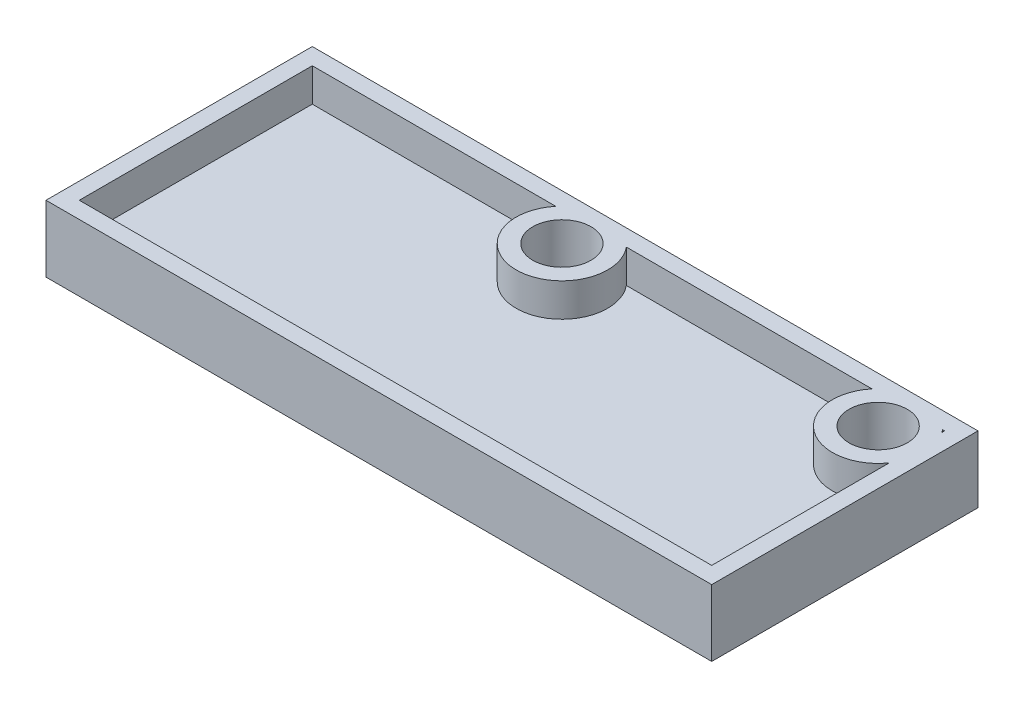
SolidWorks part; units mm, degrees
ref_plane "Front Plane" through (0, 0, 0) normal (0, 0, 1) x (1, 0, 0)
ref_plane "Top Plane" through (0, 0, 0) normal (0, 1, 0) x (1, 0, 0)
ref_plane "Right Plane" through (0, 0, 0) normal (1, 0, 0) x (0, 0, -1)
sketch "Sketch1" plane through (0, 0, 0) normal (0, 1, 0) x (1, 0, 0)
  line L1 (0, 0) -> (40, 0)
  line L2 (0, 0) -> (0, 16)
  line L3 (0, 16) -> (40, 16)
  line L4 (40, 0) -> (40, 16)
  dimension "D1" = 40
  dimension "D2" = 16
extrude "Boss-Extrude1" add sketch "Sketch1" along normal blind 2
sketch "Sketch2" plane through (0, 2, 0) normal (0, 1, 0) x (1, 0, 0)
  line L1 (0, 0) -> (40, 0)
  line L2 (0, 0) -> (0, 16)
  line L3 (0, 16) -> (40, 16)
  line L4 (40, 0) -> (40, 16)
  line L5 (1, 1) -> (39, 1)
  line L6 (1, 1) -> (1, 15)
  line L7 (1, 15) -> (39, 15)
  line L8 (39, 1) -> (39, 15)
  dimension "D1" = 1
  dimension "D2" = 1
  dimension "D3" = 14
  dimension "D4" = 38
extrude "Boss-Extrude2" add sketch "Sketch2" along normal blind 2
sketch "Sketch3" plane through (0, 4, 0) normal (0, 1, 0) x (1, 0, 0)
  line L0 (17.75, 13.25) -> (17.75, 16)
  line L1 (17.75, 16) -> (40, 16)
  line L2 (40, 16) -> (40, 0)
  line L3 (40, 0) -> (0.5, 0)
  line L4 (0.5, 0) -> (0.5, 16)
  line L5 (0.5, 16) -> (17.75, 16)
  line L6 (36.75, 16) -> (36.75, 13.25)
  line L7 (17.75, 13.25) -> (36.75, 13.25)
  line L8 (36.75, 13.25) -> (40, 13.25)
  line L9 (0, 0) -> (40, 0) construction
  line L10 (40, 0) -> (40, 16) construction
  circle A0 centre (36.75, 13.25) radius 1.75
  circle A1 centre (17.75, 13.25) radius 1.75
  circle A2 centre (17.75, 13.25) radius 2.75
  circle A3 centre (36.75, 13.25) radius 2.75
  line M18 (1, 15) -> (39, 15)
  line M19 (39, 15) -> (39, 1)
  dimension "D3" = 3.5
  dimension "D7" = 3.5
  dimension "D1" = 3.25
  dimension "D2" = 2.75
  dimension "D4" = 16
  dimension "D5" = 39.5
  dimension "D6" = 17.25
  dimension "D8" = 0
  dimension "D9" = 0
  dimension "D10" = 2.75
extrude "Boss-Extrude5" add sketch "Sketch3" against normal up to next contours L7 A0 L8 | L8 A0 L6 | L6 A0 L7 | L0 A1 L7 | L7 A1 L0 | A3 L6 M18 | A3 L8 M19 | L8 A3 M19 | L6 A3 M18 | A2 L0 M18 | L0 A2 M18
sketch "Sketch4" plane through (0, 4, 0) normal (0, 1, 0) x (1, 0, 0)
  circle A0 centre (17.75, 13.25) radius 1.75
  circle A1 centre (36.75, 13.25) radius 1.75
  dimension "D1" = 3.5
  dimension "D2" = 3.5
extrude "Cut-Extrude1" cut sketch "Sketch4" against normal through all
